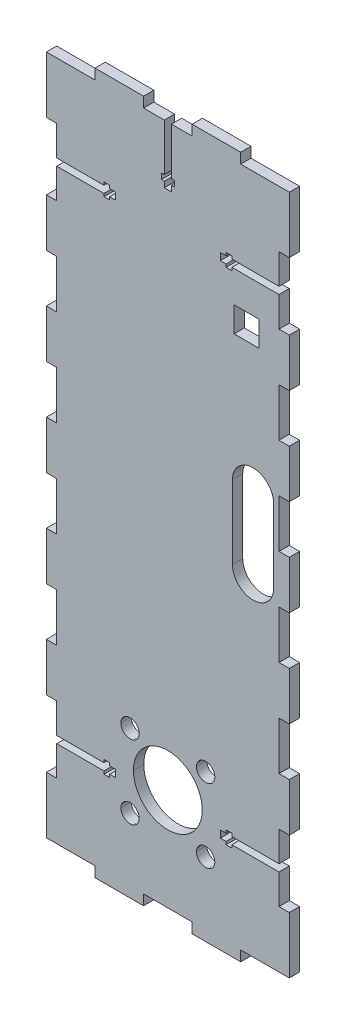
SolidWorks part; units mm, degrees
ref_plane "Front Plane" through (0, 0, 0) normal (0, 0, 1) x (1, 0, 0)
ref_plane "Top Plane" through (0, 0, 0) normal (0, 1, 0) x (1, 0, 0)
ref_plane "Right Plane" through (0, 0, 0) normal (1, 0, 0) x (0, 0, -1)
sketch "Model" plane through (0, 0, 0) normal (0, 0, 1) x (1, 0, 0)
  line L0 (718.0258, -565.5278) -> (718.0258, -552.7526)
  line L1 (718.0258, -552.7526) -> (722.5258, -552.7526)
  line L2 (722.5258, -552.7526) -> (722.5257, -528.0027)
  line L3 (718.0258, -783.7776) -> (718.0258, -771.0025)
  line L4 (718.0258, -771.0025) -> (722.5258, -771.0025)
  line L5 (722.5258, -771.0025) -> (722.5258, -750.0026)
  line L6 (722.5258, -750.0026) -> (718.0258, -750.0026)
  line L7 (718.0258, -750.0026) -> (718.0258, -729.0027)
  line L8 (718.0258, -729.0027) -> (722.5258, -729.0027)
  line L9 (722.5258, -729.0027) -> (722.5258, -708.0028)
  line L10 (722.5258, -708.0028) -> (718.0258, -708.0028)
  line L11 (718.0258, -708.0028) -> (718.0258, -687.0025)
  line L12 (718.0258, -687.0025) -> (722.5258, -687.0025)
  line L13 (722.5258, -687.0025) -> (722.5258, -666.0026)
  line L14 (722.5258, -666.0026) -> (718.0258, -666.0026)
  line L15 (718.0258, -666.0026) -> (718.0258, -645.0027)
  line L16 (718.0258, -645.0027) -> (722.5258, -645.0027)
  line L17 (722.5258, -645.0027) -> (722.5258, -624.0028)
  line L18 (722.5258, -624.0028) -> (718.0258, -624.0028)
  line L19 (718.0258, -624.0028) -> (718.0258, -603.0025)
  line L20 (718.0258, -603.0025) -> (722.5258, -603.0025)
  line L21 (722.5258, -603.0025) -> (722.5258, -582.0025)
  line L22 (722.5258, -582.0025) -> (718.0258, -582.0025)
  line L23 (718.0258, -582.0025) -> (718.0258, -569.2278)
  line L24 (722.5257, -825.0025) -> (722.5258, -800.2528)
  line L25 (722.5258, -800.2528) -> (718.0258, -800.2528)
  line L26 (718.0258, -800.2528) -> (718.0258, -787.4777)
  line L27 (722.5257, -825.0025) -> (701.3253, -825.0025)
  line L28 (701.3253, -825.0025) -> (701.3253, -829.5025)
  line L29 (701.3253, -829.5025) -> (680.1256, -829.5025)
  line L30 (680.1256, -829.5025) -> (680.1256, -825.0025)
  line L31 (680.1256, -825.0025) -> (671.0753, -825.0025)
  line L32 (718.0258, -784.0775) -> (697.4254, -784.0775)
  line L33 (697.4254, -784.0775) -> (697.4254, -782.8277)
  line L34 (697.4254, -782.8277) -> (694.9257, -782.8277)
  line L35 (694.9257, -782.8277) -> (694.9257, -784.0775)
  line L36 (694.9257, -784.0775) -> (692.4252, -784.0775)
  line L37 (692.4252, -784.0775) -> (692.4252, -787.1774)
  line L38 (692.4252, -787.1774) -> (694.9257, -787.1774)
  line L39 (694.9257, -787.1774) -> (694.9257, -788.4273)
  line L40 (694.9257, -788.4273) -> (697.4254, -788.4273)
  line L41 (697.4254, -788.4273) -> (697.4254, -787.1774)
  line L42 (697.4254, -787.1774) -> (718.0258, -787.1774)
  line L43 (718.0258, -565.8275) -> (697.4254, -565.8275)
  line L44 (697.4254, -565.8275) -> (697.4254, -564.5776)
  line L45 (697.4254, -564.5776) -> (694.9257, -564.5776)
  line L46 (694.9257, -564.5776) -> (694.9257, -565.8275)
  line L47 (694.9257, -565.8275) -> (692.4252, -565.8275)
  line L48 (692.4252, -565.8275) -> (692.4252, -568.9277)
  line L49 (692.4252, -568.9277) -> (694.9257, -568.9277)
  line L50 (694.9257, -568.9277) -> (694.9257, -570.1776)
  line L51 (694.9257, -570.1776) -> (697.4254, -570.1776)
  line L52 (697.4254, -570.1776) -> (697.4254, -568.9277)
  line L53 (697.4254, -568.9277) -> (718.0258, -568.9277)
  line L54 (667.9754, -825.0025) -> (658.9251, -825.0025)
  line L55 (658.9251, -825.0025) -> (658.9251, -829.5025)
  line L56 (658.9251, -829.5025) -> (637.7256, -829.5025)
  line L57 (637.7256, -829.5025) -> (637.7256, -825.0025)
  line L58 (637.7256, -825.0025) -> (616.5255, -825.0025)
  line L59 (616.5255, -825.0025) -> (616.5255, -800.253)
  line L60 (616.5255, -800.253) -> (621.0254, -800.253)
  line L61 (621.0254, -800.253) -> (621.0254, -787.1774)
  line L62 (621.0254, -787.1774) -> (641.6254, -787.1774)
  line L63 (641.6254, -787.1774) -> (641.6254, -788.4273)
  line L64 (641.6254, -788.4273) -> (644.1255, -788.4273)
  line L65 (644.1255, -788.4273) -> (644.1255, -787.1774)
  line L66 (644.1255, -787.1774) -> (646.6254, -787.1774)
  line L67 (646.6254, -787.1774) -> (646.6254, -784.0775)
  line L68 (646.6254, -784.0775) -> (644.1255, -784.0775)
  line L69 (644.1255, -784.0775) -> (644.1255, -782.8277)
  line L70 (644.1255, -782.8277) -> (641.6254, -782.8277)
  line L71 (641.6254, -782.8277) -> (641.6254, -784.0775)
  line L72 (641.6254, -784.0775) -> (621.0254, -784.0775)
  line L73 (621.0254, -784.0775) -> (621.0254, -771.0027)
  line L74 (621.0254, -771.0027) -> (616.5255, -771.0027)
  line L75 (616.5255, -771.0027) -> (616.5255, -750.0028)
  line L76 (616.5255, -750.0028) -> (621.0254, -750.0028)
  line L77 (621.0254, -750.0028) -> (621.0254, -729.0029)
  line L78 (621.0254, -729.0029) -> (616.5255, -729.0029)
  line L79 (616.5255, -729.0029) -> (616.5255, -708.0028)
  line L80 (616.5255, -708.0028) -> (621.0254, -708.0028)
  line L81 (621.0254, -708.0028) -> (621.0254, -687.0025)
  line L82 (621.0254, -687.0025) -> (616.5255, -687.0025)
  line L83 (616.5255, -687.0025) -> (616.5255, -666.0026)
  line L84 (616.5255, -666.0026) -> (621.0254, -666.0026)
  line L85 (621.0254, -666.0026) -> (621.0254, -645.0027)
  line L86 (621.0254, -645.0027) -> (616.5255, -645.0027)
  line L87 (616.5255, -645.0027) -> (616.5255, -624.0028)
  line L88 (616.5255, -624.0028) -> (621.0254, -624.0028)
  line L89 (621.0254, -624.0028) -> (621.0254, -603.0025)
  line L90 (621.0254, -603.0025) -> (616.5255, -603.0025)
  line L91 (616.5255, -603.0025) -> (616.5255, -582.0025)
  line L92 (616.5255, -582.0025) -> (621.0254, -582.0025)
  line L93 (621.0254, -582.0025) -> (621.0254, -568.9277)
  line L94 (621.0254, -568.9277) -> (641.6254, -568.9277)
  line L95 (641.6254, -568.9277) -> (641.6254, -570.1776)
  line L96 (641.6254, -570.1776) -> (644.1255, -570.1776)
  line L97 (644.1255, -570.1776) -> (644.1255, -568.9277)
  line L98 (644.1255, -568.9277) -> (646.6254, -568.9277)
  line L99 (646.6254, -568.9277) -> (646.6254, -565.8275)
  line L100 (646.6254, -565.8275) -> (644.1255, -565.8275)
  line L101 (644.1255, -565.8275) -> (644.1255, -564.5776)
  line L102 (644.1255, -564.5776) -> (641.6254, -564.5776)
  line L103 (641.6254, -564.5776) -> (641.6254, -565.8275)
  line L104 (641.6254, -565.8275) -> (621.0254, -565.8275)
  line L105 (621.0254, -565.8275) -> (621.0254, -552.7526)
  line L106 (621.0254, -552.7526) -> (616.5255, -552.7526)
  line L107 (616.5255, -552.7526) -> (616.5255, -528.0027)
  line L108 (616.5255, -528.0027) -> (637.7256, -528.0027)
  line L109 (637.7256, -528.0027) -> (637.7256, -523.5027)
  line L110 (637.7256, -523.5027) -> (658.9251, -523.5027)
  line L111 (658.9251, -523.5027) -> (658.9251, -528.0027)
  line L112 (658.9251, -528.0027) -> (667.9754, -528.0027)
  line L113 (667.9754, -528.0027) -> (667.9754, -548.6027)
  line L114 (667.9754, -548.6027) -> (666.7255, -548.6027)
  line L115 (666.7255, -548.6027) -> (666.7255, -551.1028)
  line L116 (666.7255, -551.1028) -> (667.9754, -551.1028)
  line L117 (667.9754, -551.1028) -> (667.9754, -553.6026)
  line L118 (667.9754, -553.6026) -> (671.0753, -553.6026)
  line L119 (671.0753, -553.6026) -> (671.0753, -551.1028)
  line L120 (671.0753, -551.1028) -> (672.3252, -551.1028)
  line L121 (672.3252, -551.1028) -> (672.3252, -548.6027)
  line L122 (672.3252, -548.6027) -> (671.0753, -548.6027)
  line L123 (671.0753, -548.6027) -> (671.0753, -528.0027)
  line L124 (671.0753, -528.0027) -> (680.1256, -528.0027)
  line L125 (680.1256, -528.0027) -> (680.1256, -523.5027)
  line L126 (680.1256, -523.5027) -> (701.3253, -523.5027)
  line L127 (701.3253, -523.5027) -> (701.3253, -528.0027)
  line L128 (701.3253, -528.0027) -> (722.5257, -528.0027)
  line L129 (715.6996, -681.0851) -> (715.6996, -649.0178)
  line L130 (697.7079, -649.0178) -> (697.7079, -681.0851)
  line L131 (667.9754, -825.0025) -> (671.0753, -825.0025)
  line L132 (709.414, -593.6039) -> (698.4139, -593.6039)
  line L133 (698.4139, -593.6039) -> (698.4139, -582.6039)
  line L134 (698.4139, -582.6039) -> (709.414, -582.6039)
  line L135 (709.414, -582.6039) -> (709.414, -593.6039)
  line L136 (718.0258, -568.9277) -> (718.0258, -569.2278)
  line L137 (718.0258, -565.8275) -> (718.0258, -565.5278)
  line L138 (718.0258, -787.4777) -> (718.0258, -787.1774)
  line L139 (718.0258, -784.0775) -> (718.0258, -783.7776)
  spline S0 degree 3 poles (654.5188, -780.5232) (654.5188, -772.2388) (661.2344, -765.5233) (669.5188, -765.5233) (677.8032, -765.5233) (684.5187, -772.2388) (684.5187, -780.5232) knots 2 2 2 2 3 3 3 4 4 4 4
  spline S1 degree 3 poles (684.5187, -780.5232) (684.5187, -788.8077) (677.8032, -795.5232) (669.5188, -795.5232) (661.2344, -795.5232) (654.5188, -788.8077) (654.5188, -780.5232) knots 0 0 0 0 1 1 1 2 2 2 2
  spline S2 degree 3 poles (682.0204, -797.4566) (682.0204, -795.2472) (683.8111, -793.4565) (686.0201, -793.4565) (688.2291, -793.4565) (690.0199, -795.2472) (690.0199, -797.4566) knots 2 2 2 2 3 3 3 4 4 4 4
  spline S3 degree 3 poles (690.0199, -797.4566) (690.0199, -799.6656) (688.2291, -801.4567) (686.0201, -801.4567) (683.8111, -801.4567) (682.0204, -799.6656) (682.0204, -797.4566) knots 0 0 0 0 1 1 1 2 2 2 2
  spline S4 degree 3 poles (682.0204, -765.3538) (682.0204, -763.1444) (683.8111, -761.3537) (686.0201, -761.3537) (688.2291, -761.3537) (690.0199, -763.1444) (690.0199, -765.3538) knots 2 2 2 2 3 3 3 4 4 4 4
  spline S5 degree 3 poles (690.0199, -765.3538) (690.0199, -767.5628) (688.2291, -769.3539) (686.0201, -769.3539) (683.8111, -769.3539) (682.0204, -767.5628) (682.0204, -765.3538) knots 0 0 0 0 1 1 1 2 2 2 2
  spline S6 degree 3 poles (649.0308, -765.3538) (649.0308, -763.1444) (650.8219, -761.3537) (653.0312, -761.3537) (655.2403, -761.3537) (657.031, -763.1444) (657.031, -765.3538) knots 2 2 2 2 3 3 3 4 4 4 4
  spline S7 degree 3 poles (657.031, -765.3538) (657.031, -767.5628) (655.2403, -769.3539) (653.0312, -769.3539) (650.8219, -769.3539) (649.0308, -767.5628) (649.0308, -765.3538) knots 0 0 0 0 1 1 1 2 2 2 2
  spline S8 degree 3 poles (649.0308, -797.4566) (649.0308, -795.2472) (650.8219, -793.4565) (653.0312, -793.4565) (655.2403, -793.4565) (657.031, -795.2472) (657.031, -797.4566) knots 2 2 2 2 3 3 3 4 4 4 4
  spline S9 degree 3 poles (657.031, -797.4566) (657.031, -799.6656) (655.2403, -801.4567) (653.0312, -801.4567) (650.8219, -801.4567) (649.0308, -799.6656) (649.0308, -797.4566) knots 0 0 0 0 1 1 1 2 2 2 2
  spline S10 degree 3 poles (697.7079, -649.0178) (697.7672, -644.0819) (701.7683, -640.0808) (706.7038, -640.0808) (711.6399, -640.0808) (715.641, -644.0819) (715.6996, -649.0178) knots 0 0 0 0 1 1 1 2 2 2 2
  spline S11 degree 3 poles (697.7079, -681.0851) (697.7079, -686.0532) (701.736, -690.0809) (706.7038, -690.0809) (711.6723, -690.0809) (715.6996, -686.0532) (715.6996, -681.0851) knots 0 0 0 0 1 1 1 2 2 2 2
extrude "Boss-Extrude1" add sketch "Model" along normal blind 4.5
